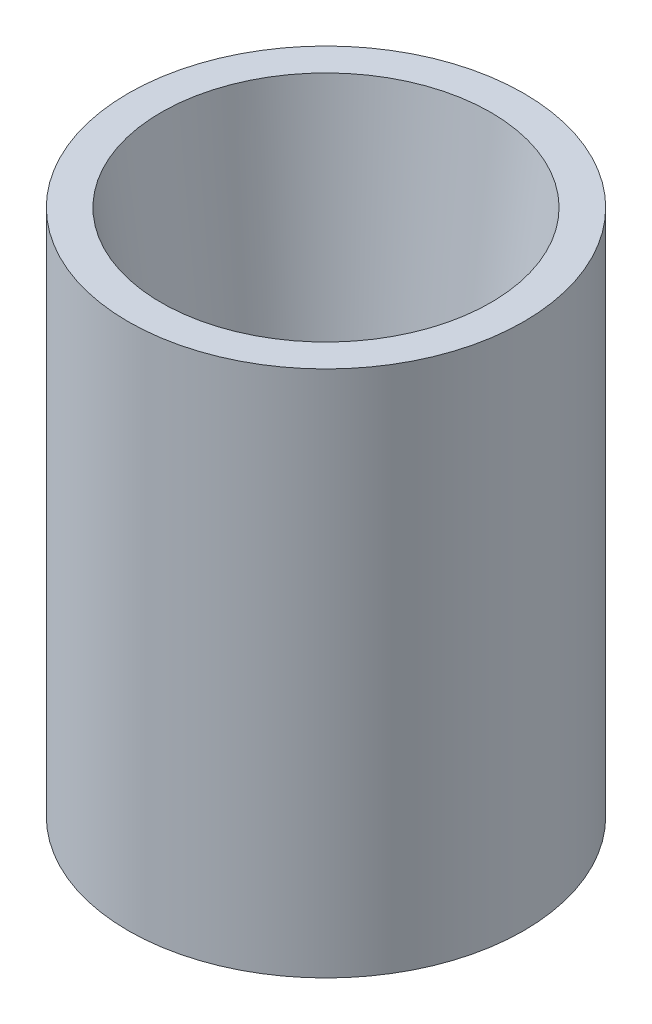
SolidWorks part; units mm, degrees
material "1060 Alloy"
ref_plane "Front Plane" through (0, 0, 0) normal (0, 0, 1) x (1, 0, 0)
ref_plane "Top Plane" through (0, 0, 0) normal (0, 1, 0) x (1, 0, 0)
ref_plane "Right Plane" through (0, 0, 0) normal (1, 0, 0) x (0, 0, -1)
sketch "Sketch1" plane through (0, 0, 0) normal (0, 0, 1) x (1, 0, 0)
  line L0 (0, 0) -> (0, 92.7267) construction
  line L1 (0, 0) -> (30, 0)
  line L2 (30, 0) -> (30, 80)
  line L3 (30, 80) -> (0, 80)
  line L4 (0, 0) -> (0, 80)
  dimension "D1" = 60
  dimension "D2" = 80
revolve "Revolve1" add sketch "Sketch1" angle 360 about L0
sketch "Sketch3" plane through (0, 0, 0) normal (0, 0, 1) x (1, 0, 0)
  line L0 (0, 0) -> (0, 113.2499) construction
  line L1 (0, 10) -> (16.4051, 10)
  line L2 (16.4051, 10) -> (25, 80)
  line L3 (25, 80) -> (0, 80)
  line L4 (30, 80) -> (-30, 80) construction
  line L5 (-30, 0) -> (30, 0) construction
  line L6 (0, 10) -> (0, 80)
  dimension "D1" = 10
  dimension "D2" = 5
  dimension "D3" = 7
revolve "Cut-Revolve1" cut sketch "Sketch3" angle 360 about L0
